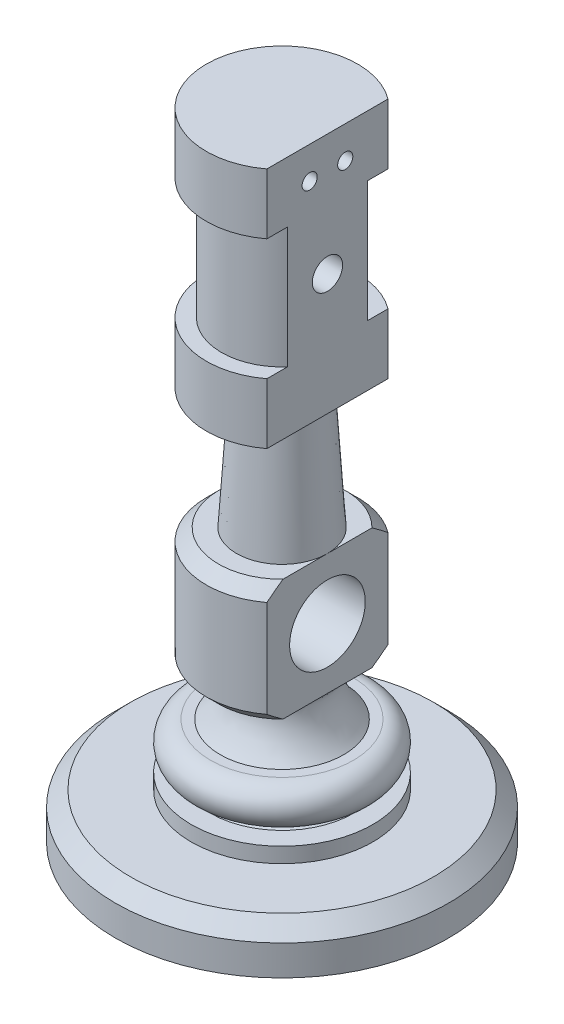
SolidWorks part; units mm, degrees
ref_plane "Front Plane" through (0, 0, 0) normal (0, 0, 1) x (1, 0, 0)
ref_plane "Top Plane" through (0, 0, 0) normal (0, 1, 0) x (1, 0, 0)
ref_plane "Right Plane" through (0, 0, 0) normal (1, 0, 0) x (0, 0, -1)
sketch "Sketch1" plane through (0, 0, 0) normal (1, 0, 0) x (0, 0, -1)
  line L0 (0, 73.6173) -> (0, -12.4366) construction
  line L1 (0, 0) -> (-17.4625, 0)
  line L2 (-17.4625, 0) -> (-17.4625, 4.7625)
  line L3 (-17.4625, 4.7625) -> (0, 4.7625)
  line L4 (-9.525, 4.7625) -> (-9.525, 6.35)
  line L5 (-9.525, 6.35) -> (0, 6.35)
  line L7 (-7.493, 15.875) -> (0, 15.875)
  line L8 (-7.493, 15.875) -> (-7.9375, 15.875)
  line L9 (-7.9375, 15.875) -> (-7.9375, 28.575)
  line L10 (-7.9375, 28.575) -> (0, 28.575)
  line L11 (-4.7625, 28.575) -> (-3.9687, 41.275)
  line L12 (-3.9687, 41.275) -> (-7.9375, 41.275)
  line L13 (-7.9375, 41.275) -> (-7.9375, 47.625)
  line L14 (-7.9375, 47.625) -> (-6.35, 47.625)
  line L15 (-6.35, 47.625) -> (-6.35, 60.325)
  line L16 (-6.35, 60.325) -> (-7.9375, 60.325)
  line L17 (-7.9375, 60.325) -> (-7.9375, 66.675)
  line L18 (-7.9375, 66.675) -> (0, 66.675)
  line L19 (-3.9687, 41.275) -> (0, 41.275)
  line L20 (-7.493, 11.1652) -> (0, 11.1652)
  arc A0 (-7.493, 11.1652) -> (-7.493, 7.1012) centre (-7.493, 9.1332) ccw
  arc A1 (-7.493, 7.1012) -> (-7.493, 6.35) centre (-7.6115, 6.7256) cw
  spline S0 degree 3 poles (-4.7625, 15.875) (-4.5992, 15.6738) (-4.5292, 15.2193) (-4.602, 14.6594) (-4.8637, 13.2096) (-5.693, 11.9445) (-6.477, 11.1652) knots 0 0 0 0 0.134423 0.277975 0.329407 1 1 1 1
  dimension "D1" = 17.4625
  dimension "D2" = 9.525
  dimension "D3" = 1.5875
  dimension "D5" = 11.1125
  dimension "D6" = 4.7625
  dimension "D7" = 7.9375
  dimension "D8" = 12.7
  dimension "D9" = 12.7
  dimension "D10" = 4.7625
  dimension "D11" = 3.9688
  dimension "D12" = 6.35
  dimension "D13" = 7.9375
  dimension "D14" = 6.35
  dimension "D15" = 12.7
  dimension "D16" = 6.35
  dimension "D17" = 7.9375
  dimension "D18" = 6.477
  dimension "D19" = 4.7625
revolve "Revolve1" add sketch "Sketch1" angle 360 about L0
chamfer "Chamfer1" distance 1.5875 angle 45 1 edges at (0, 4.7625, 17.4625)
chamfer "Chamfer2" distance 1.27 angle 45 2 edges at (0, 15.875, 7.9375) (0, 28.575, 7.9375)
sketch "Sketch2" plane through (0, 0, 0) normal (1, 0, 0) x (0, 0, -1)
  line L0 (6.6675, 28.575) -> (-6.6675, 28.575) construction
  line L1 (0, 74.2974) -> (0, -20.152) construction
  line L2 (-6.35, 60.325) -> (6.35, 60.325) construction
  line L3 (7.9375, 66.675) -> (-7.9375, 66.675) construction
  circle A0 centre (0, 22.225) radius 3.9688
  circle A1 centre (0, 53.975) radius 1.5875
  circle A2 centre (-1.865, 63.308) radius 0.7937
  circle A3 centre (1.865, 63.308) radius 0.7937
  circle A4 centre (0, 53.975) radius 3.175
  dimension "D1" = 7.9375
  dimension "D3" = 3.175
  dimension "D7" = 1.5875
  dimension "D8" = 6.35
  dimension "D2" = 6.35
  dimension "D4" = 6.35
  dimension "D5" = 3.73
  dimension "D6" = 3.367
extrude "Cut-Extrude4" cut sketch "Sketch2" against normal up to next and the other way up to next contours A3 | A2 | A1 | A0
sketch "Sketch3" plane through (0, 0, 0) normal (1, 0, 0) x (0, 0, -1)
  circle A0 centre (0, 53.975) radius 3.175
  dimension "D1" = 6.35
extrude "Cut-Extrude5" cut sketch "Sketch3" against normal up to next
sketch "Sketch5" plane through (0, 66.675, 0) normal (0, 1, 0) x (1, 0, 0)
  line L4 (0, 14.0586) -> (0, -13.0305)
  line L5 (7.9375, -10.2749) -> (4.7625, -10.2749)
  line L6 (7.9375, 10.7021) -> (4.7625, 10.7021)
  line L7 (7.9375, 10.7021) -> (7.9375, -10.2749)
  line L8 (4.7625, 10.7021) -> (4.7625, -10.2749)
  circle M5 centre (0, 0) radius 7.9375
extrude "Cut-Extrude7" cut sketch "Sketch5" against normal blind 50.8 contours L6 L8 L7 M5 | L8 M5 | L8 L5 L7 M5
